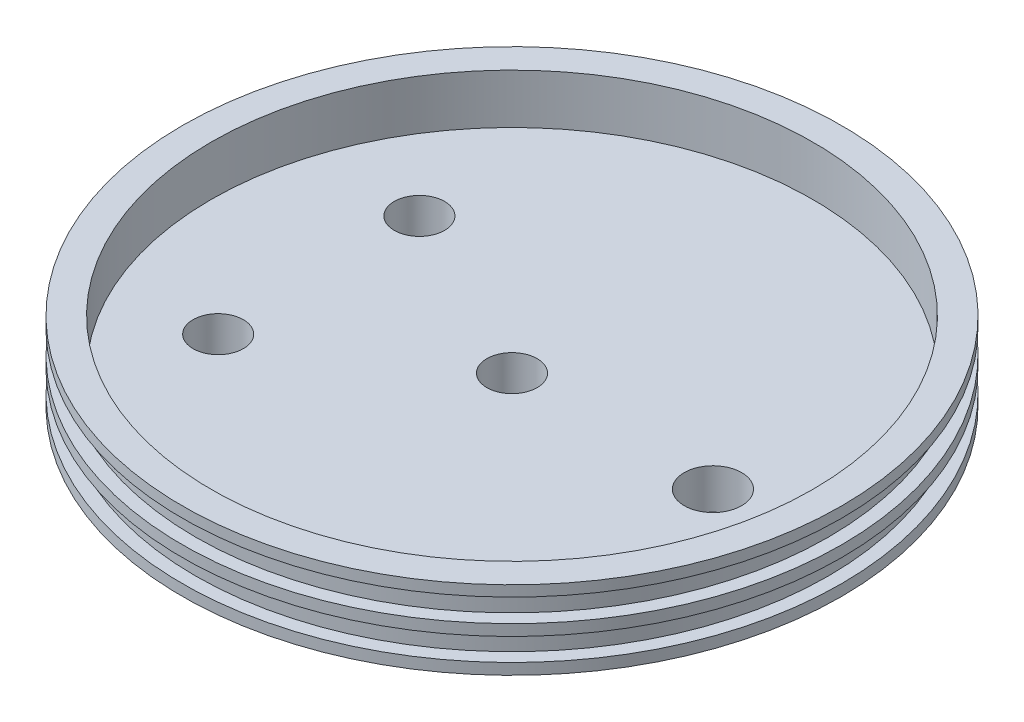
SolidWorks part; units mm, degrees
material "6061-T6 (SS)"
ref_plane "Front Plane" through (0, 0, 0) normal (0, 0, 1) x (1, 0, 0)
ref_plane "Top Plane" through (0, 0, 0) normal (0, 1, 0) x (1, 0, 0)
ref_plane "Right Plane" through (0, 0, 0) normal (1, 0, 0) x (0, 0, -1)
sketch "Sketch1" plane through (0, 0, 0) normal (0, 0, 1) x (1, 0, 0)
  line L0 (0, 48.1922) -> (0, -25.6743) construction
  line L1 (0, 0) -> (72.898, 0)
  line L2 (72.898, 0) -> (72.898, 2.4638)
  line L3 (72.898, 2.4638) -> (69.977, 2.4638)
  line L4 (69.977, 2.4638) -> (69.977, 7.4422)
  line L5 (69.977, 7.4422) -> (72.898, 7.4422)
  line L6 (72.898, 7.4422) -> (72.898, 9.906)
  line L7 (72.898, 9.906) -> (69.977, 9.906)
  line L8 (66.548, 17.3482) -> (66.548, 6.35)
  line L9 (66.548, 6.35) -> (0, 6.35)
  line L10 (0, 6.35) -> (0, 0)
  line L11 (69.977, 9.906) -> (69.977, 14.986)
  line L12 (69.977, 14.986) -> (72.898, 14.986)
  line L13 (72.898, 14.986) -> (72.898, 17.3482)
  line L14 (72.898, 17.3482) -> (66.548, 17.3482)
  point P15 (41.148, 16.9853)
  dimension "D1" = 145.796
  dimension "D2" = 4.9784
  dimension "D3" = 2.921
  dimension "D4" = 9.906
  dimension "D5" = 6.35
  dimension "D6" = 6.35
  dimension "D7" = 5.08
  dimension "D8" = 9.906
revolve "Revolve1" add sketch "Sketch1" angle 360 about L0
sketch "Sketch6" plane through (0, 0, 0) normal (0, -1, 0) x (1, 0, 0)
  circle A0 centre (0, 0) radius 66.04
  dimension "D1" = 132.08
extrude "Boss-Extrude1" add sketch "Sketch6" along normal blind 2.54
hole_wizard "Pipe Tap Drill for 1/4 Tap - GN2" positions "Sketch2" profile "Sketch3" hole size "1/4" standard "ANSI Inch" end condition through all
sketch "Sketch2" plane through (0, 6.35, 0) normal (0, 1, 0) x (1, 0, 0)
  point P4 (0, 0)
  dimension "D1" = 0
sketch "Sketch3" plane through (0, 6.35, 0) normal (1, 0, 0) x (0, 0, 1)
  line L0 (0, 0) -> (0, 8.89)
  line L1 (0, 8.89) -> (5.5626, 8.89)
  line L2 (5.5626, 8.89) -> (5.5626, 0)
  line L5 (5.5626, 0) -> (0, 0)
  line L11 (0, -6.35) -> (0, 107.95) construction
  dimension "Thru Hole Dia." = 11.1252
  dimension "Thru Hole Depth" = 8.89
fillet "CNC ID Fillet" [suppressed] radius 0.1778
fillet "CNC OD Fillet" [suppressed] radius 0.127
chamfer "CNC Chamfers" [suppressed] distance 0.254 angle 45
fillet "CNC Bore Fillet" [suppressed] radius 0.254
sketch "Sketch7" plane through (0, -2.54, 0) normal (0, -1, 0) x (-1, 0, 0)
  circle A0 centre (-44.45, 0) radius 6.35
  point P5 (0, 0)
  dimension "D1" = 12.7
  dimension "D2" = 44.45
extrude "Cut-Extrude1-Siphon" cut sketch "Sketch7" against normal through all
hole_wizard "Pipe Tap Drill for 1/4 Tap - Relief Valve" positions "Sketch13" profile "Sketch14" hole size "1/4" standard "ANSI Inch" end condition through all
sketch "Sketch13" plane through (0, -2.54, 0) normal (0, -1, 0) x (-1, 0, 0)
  point P4 (40.358, 19.8786)
sketch "Sketch14" plane through (-40.358, -2.54, -19.8786) normal (1, 0, 0) x (0, 0, -1)
  line L0 (0, 0) -> (0, 19.8882)
  line L1 (0, 19.8882) -> (5.5626, 19.8882)
  line L2 (5.5626, 19.8882) -> (5.5626, 0)
  line L5 (5.5626, 0) -> (0, 0)
  line L11 (0, -6.35) -> (0, 107.95) construction
  dimension "Thru Hole Dia." = 11.1252
  dimension "Thru Hole Depth" = 19.8882
hole_wizard "Pipe Tap Drill for 1/4 Tap - Vent Valve" positions "Sketch15" profile "Sketch16" hole size "1/4" standard "ANSI Inch" end condition through all
sketch "Sketch15" plane through (0, -2.54, 0) normal (0, -1, 0) x (-1, 0, 0)
  point P4 (39.9614, -25.0312)
sketch "Sketch16" plane through (-39.9614, -2.54, 25.0312) normal (1, 0, 0) x (0, 0, -1)
  line L0 (0, 0) -> (0, 19.8882)
  line L1 (0, 19.8882) -> (5.5626, 19.8882)
  line L2 (5.5626, 19.8882) -> (5.5626, 0)
  line L5 (5.5626, 0) -> (0, 0)
  line L11 (0, -6.35) -> (0, 107.95) construction
  dimension "Thru Hole Dia." = 11.1252
  dimension "Thru Hole Depth" = 19.8882
